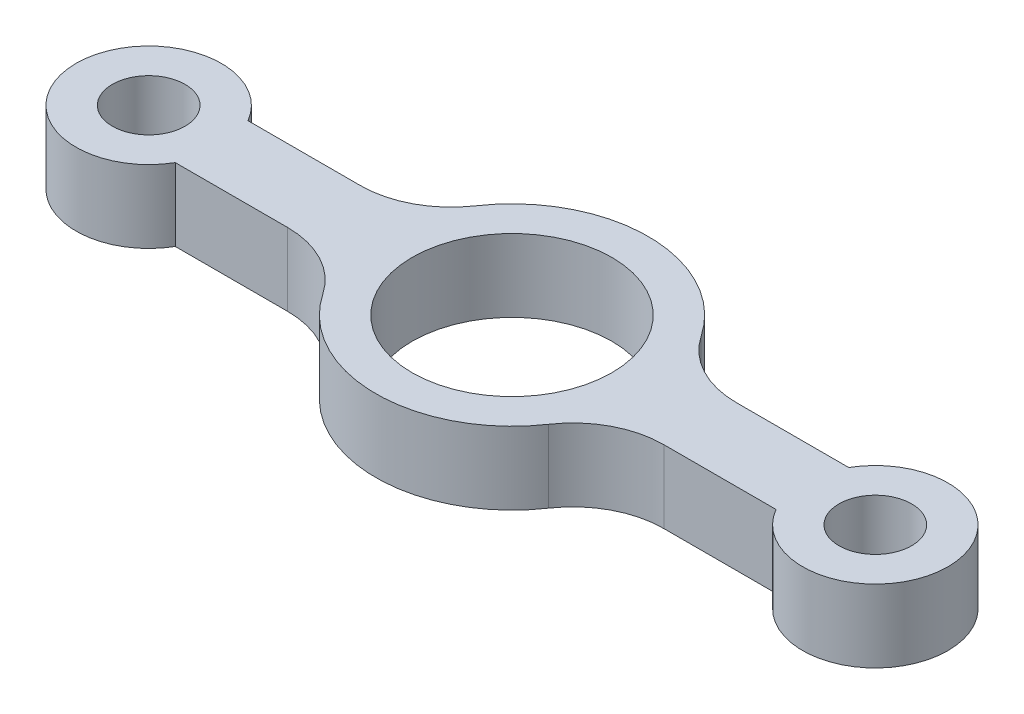
SolidWorks part; units mm, degrees
material "ABS"
ref_plane "Plano frontal" through (0, 0, 0) normal (0, 0, 1) x (1, 0, 0)
ref_plane "Plano superior" through (0, 0, 0) normal (0, 1, 0) x (1, 0, 0)
ref_plane "Plano direito" through (0, 0, 0) normal (1, 0, 0) x (0, 0, -1)
sketch "Esboço1" plane through (0, 0, 0) normal (0, 1, 0) x (1, 0, 0)
  line L0 (-40, 0) -> (40, 0) construction
  line L1 (-33.0718, 4) -> (-20.7123, 4)
  line L2 (-33.0718, -4) -> (-20.7123, -4)
  line L3 (20.7123, 4) -> (33.0718, 4)
  line L4 (20.7123, -4) -> (33.0718, -4)
  arc A0 (-33.0718, 4) -> (-33.0718, -4) centre (-40, 0) ccw
  arc A1 (33.0718, -4) -> (33.0718, 4) centre (40, 0) ccw
  circle A2 centre (40, 0) radius 4
  circle A3 centre (-40, 0) radius 4
  arc A4 (-12.4274, -8.4) -> (12.4274, -8.4) centre (0, 0) ccw
  arc A5 (12.4274, 8.4) -> (-12.4274, 8.4) centre (0, 0) ccw
  circle A6 centre (0, 0) radius 11
  arc A7 (-12.4274, -8.4) -> (-20.7123, -4) centre (-20.7123, -14) ccw
  arc A8 (20.7123, -4) -> (12.4274, -8.4) centre (20.7123, -14) ccw
  arc A9 (20.7123, 4) -> (12.4274, 8.4) centre (20.7123, 14) cw
  arc A10 (-12.4274, 8.4) -> (-20.7123, 4) centre (-20.7123, 14) cw
  point P4 (0, 0)
  point P22 (14.4568, 4)
  dimension "D2" = 8
  dimension "D3" = 16
  dimension "D5" = 30
  dimension "D6" = 22
  dimension "D7" = 10
  dimension "D1" = 80
  dimension "D4" = 8
extrude "Ressalto-extrusão1" add sketch "Esboço1" along normal blind 8
